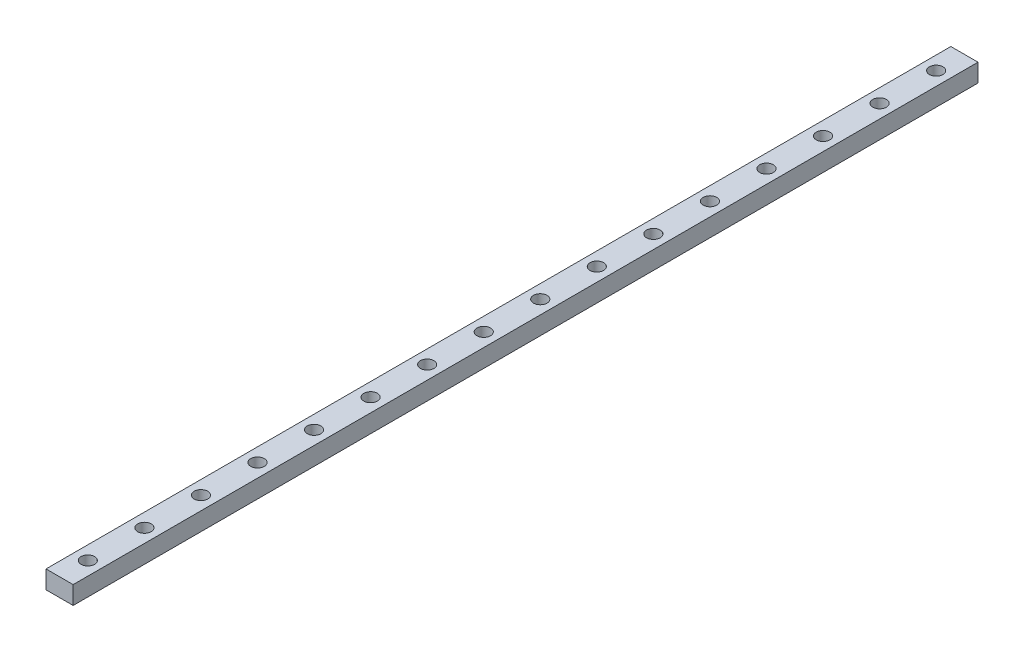
SolidWorks part; units mm, degrees
ref_plane "Front Plane" through (0, 0, 0) normal (0, 0, 1) x (1, 0, 0)
ref_plane "Top Plane" through (0, 0, 0) normal (0, 1, 0) x (1, 0, 0)
ref_plane "Right Plane" through (0, 0, 0) normal (1, 0, 0) x (0, 0, -1)
sketch "Sketch1" plane through (0, 0, 0) normal (0, 0, 1) x (1, 0, 0)
  line L1 (0, 0) -> (12, 0)
  line L2 (0, 0) -> (0, 8)
  line L3 (0, 8) -> (12, 8)
  line L4 (12, 0) -> (12, 8)
  dimension "D1" = 12
  dimension "D2" = 8
extrude "Boss-Extrude1" add sketch "Sketch1" along normal blind 400
sketch "Sketch2" plane through (0, 8, 0) normal (0, 1, 0) x (1, 0, 0)
  line L0 (12, 0) -> (0, 0) construction
  line L1 (0, -400) -> (0, 0) construction
  circle A0 centre (6, -12.5) radius 3
  dimension "D1" = 6
  dimension "D2" = 12.5
  dimension "D3" = 6
extrude "Cut-Extrude1" cut sketch "Sketch2" against normal blind 4.5
sketch "Sketch4" plane through (0, 0, 0) normal (0, -1, 0) x (1, 0, 0)
  line L0 (0, 400) -> (0, 0) construction
  line L1 (0, 0) -> (12, 0) construction
  circle A0 centre (6, 12.5) radius 1.75
  dimension "D1" = 3.5
  dimension "D2" = 6
  dimension "D3" = 12.5
extrude "Cut-Extrude2" cut sketch "Sketch4" against normal through all
pattern_linear "LPattern2" count 16 spacing 25 along (0, 0, 1) of "Cut-Extrude1", "Cut-Extrude2"
